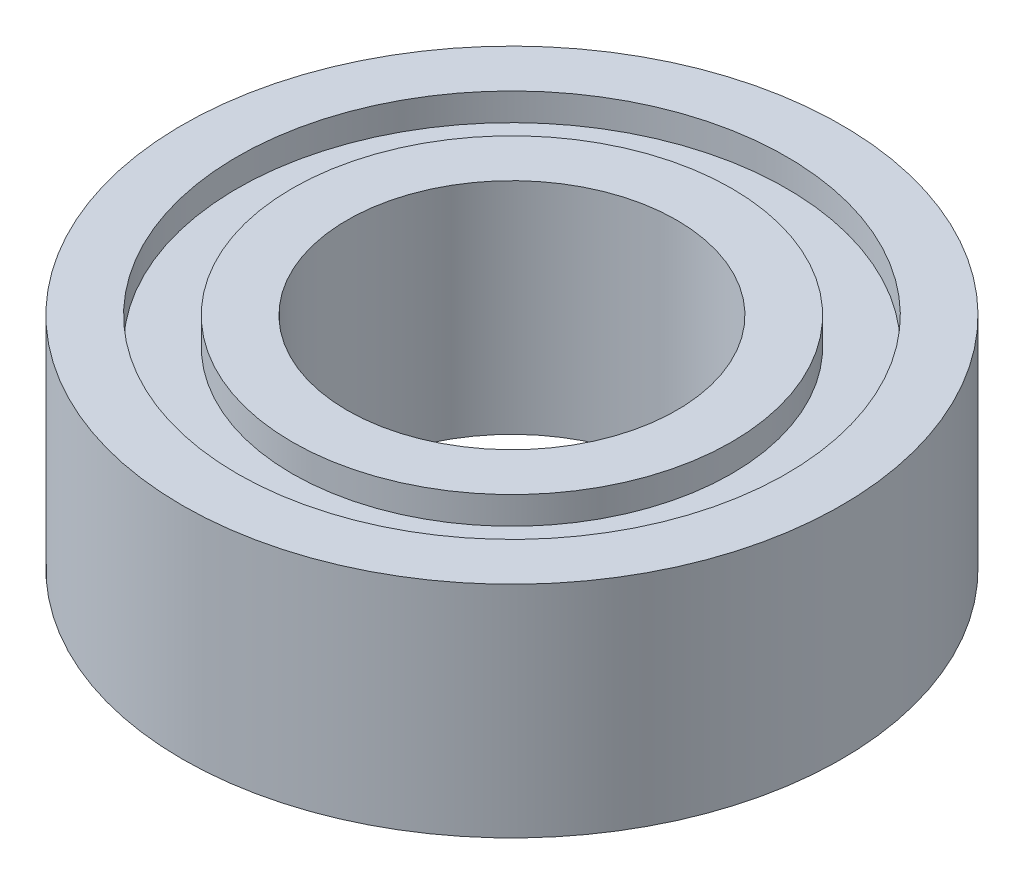
SolidWorks part; units mm, degrees
ref_plane "Front Plane" through (0, 0, 0) normal (0, 0, 1) x (1, 0, 0)
ref_plane "Top Plane" through (0, 0, 0) normal (0, 1, 0) x (1, 0, 0)
ref_plane "Right Plane" through (0, 0, 0) normal (1, 0, 0) x (0, 0, -1)
other "Configuration Table"
sketch "草图1" plane through (0, 0, 0) normal (0, 1, 0) x (1, 0, 0)
  circle A0 centre (0, 0) radius 6
  circle A1 centre (0, 0) radius 3
  dimension "D1" = 12
  dimension "D2" = 6
extrude "凸台-拉伸1" add sketch "草图1" along normal mid plane 4
sketch "草图2" plane through (0, 2, 0) normal (0, 1, 0) x (1, 0, 0)
  circle A0 centre (0, 0) radius 5
  circle A1 centre (0, 0) radius 4
  dimension "D1" = 10
  dimension "D2" = 8
extrude "切除-拉伸1" cut sketch "草图2" against normal blind 0.5
mirror "镜向1" about plane through (0, 0, 0) normal (0, 1, 0) of "切除-拉伸1"
